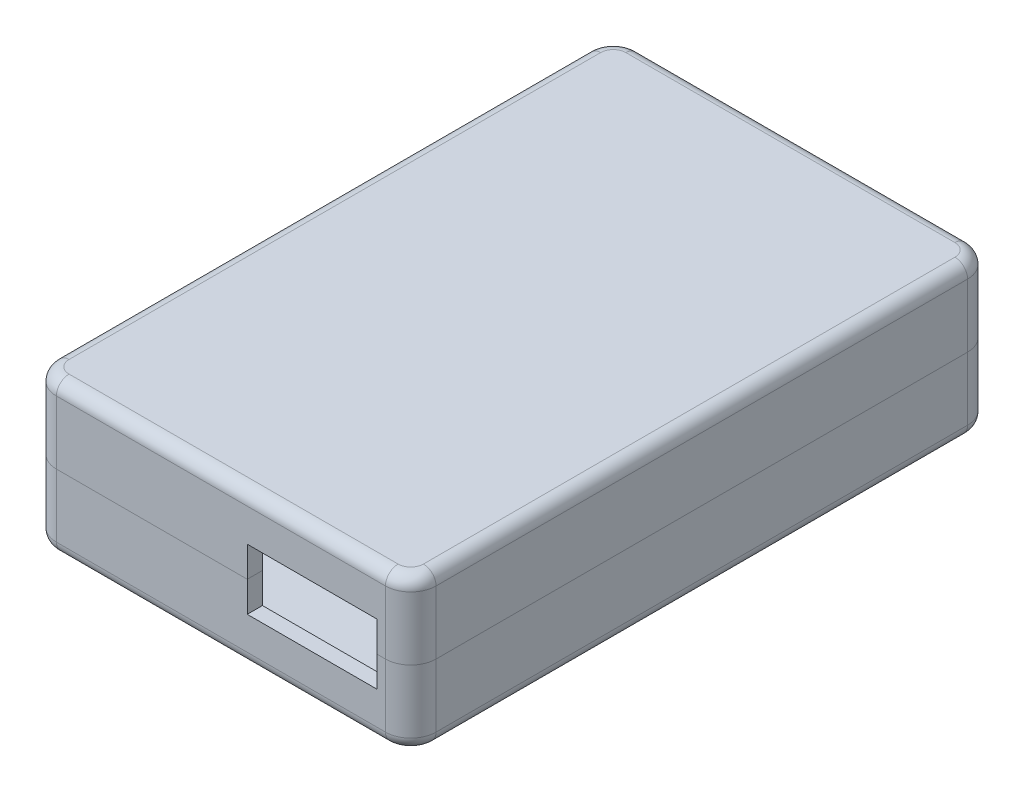
SolidWorks part; units mm, degrees
ref_plane "Front Plane" through (0, 0, 0) normal (0, 0, 1) x (1, 0, 0)
ref_plane "Top Plane" through (0, 0, 0) normal (0, 1, 0) x (1, 0, 0)
ref_plane "Right Plane" through (0, 0, 0) normal (1, 0, 0) x (0, 0, -1)
sketch "Sketch1" plane through (0, 0, 0) normal (0, 0, 1) x (1, 0, 0)
  line L0 (31, 8) -> (5, 8) construction
  line L1 (37.5, -15) -> (-37.5, -15)
  line L2 (37.5, -15) -> (37.5, 15)
  line L3 (37.5, 15) -> (-37.5, 15)
  line L4 (-37.5, -15) -> (-37.5, 15)
  line L5 (37.5, -15) -> (-37.5, 15) construction
  line L6 (37.5, 15) -> (-37.5, -15) construction
  point P0 (0, 0)
  dimension "D1" = 75
  dimension "D2" = 7
extrude "Boss-Extrude1" add sketch "Sketch1" against normal blind 115
sketch "Sketch2" plane through (0, 0, 0) normal (1, 0, 0) x (0, 0, -1)
  line L0 (-7.5, 0) -> (122.5, 0)
  line L1 (57.5, 15) -> (57.5, -15) construction
  line L2 (115, 15) -> (0, 15) construction
  line L3 (115, -15) -> (0, -15) construction
  point P9 (57.5, 0)
  dimension "D1" = 130
fillet "Fillet1" radius 5 4 edges at (37.5, 0, -115) (37.5, 0, 0) (-37.5, 0, 0) (-37.5, 0, -115)
fillet "Fillet2" radius 2.5 16 edges at (36.0355, -15, -113.5355) (0, -15, -115) (-36.0355, -15, -113.5355) (-37.5, -15, -57.5) (-36.0355, -15, -1.4645) (0, -15, 0) (36.0355, -15, -1.4645) (36.0355, 15, -113.5355) (0, 15, -115) (-36.0355, 15, -113.5355) (-37.5, 15, -57.5) (-36.0355, 15, -1.4645) (0, 15, 0) (36.0355, 15, -1.4645) (37.5, -15, -57.5) (37.5, 15, -57.5)
shell "Shell1" thickness 3
sketch "Sketch3" plane through (0, 0, 0) normal (0, 0, 1) x (1, 0, 0)
  line L0 (30.8, -6) -> (5.2, -6)
  line L1 (28.15, -6) -> (30.6332, -6) construction
  line L2 (5.3668, -6) -> (7.85, -6) construction
  line L3 (5.2, -6) -> (5.2, 6)
  line L4 (5.2, 6) -> (30.8, 6)
  line L5 (30.8, 6) -> (30.8, -6)
  line L7 (29.15, 1.5) -> (29.15, 6) construction
  line L8 (6.85, 6) -> (6.85, 3.8) construction
  dimension "D1" = 1.65
  dimension "D2" = 1.65
extrude "Cut-Extrude1" cut sketch "Sketch3" against normal blind 3
split "Split1" trim tools "Sketch2" bodies to split 104 resulting bodies 102 103
